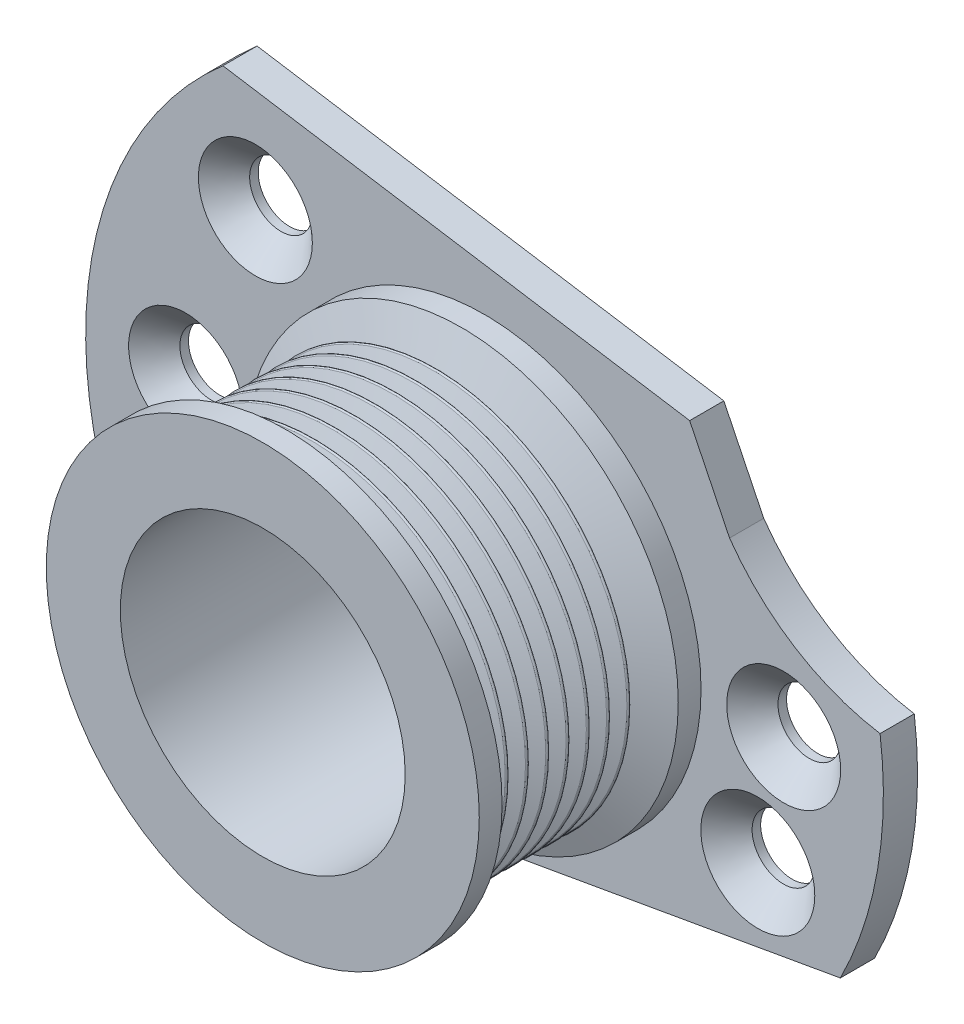
SolidWorks part; units mm, degrees
material "6061-T6 (SS)"
ref_plane "Plano frontal" through (0, 0, 0) normal (0, 0, 1) x (1, 0, 0)
ref_plane "Plano superior" through (0, 0, 0) normal (0, 1, 0) x (1, 0, 0)
ref_plane "Plano direito" through (0, 0, 0) normal (1, 0, 0) x (0, 0, -1)
sketch "Esboço1" plane through (0, 0, 0) normal (0, 0, 1) x (1, 0, 0)
  line L11 (43.3076, 46.4505) -> (-51.3624, 61.4448) construction
  line L12 (-51.3624, 61.4448) -> (-78.1924, 55.7367) construction
  line L13 (-78.1924, 55.7367) -> (-90.1924, 31.0704) construction
  line L14 (-90.1924, 31.0704) -> (-90.1924, -31.3604) construction
  line L15 (-90.1924, -31.3604) -> (-74.4201, -50.1572) construction
  line L16 (-74.4201, -50.1572) -> (-51.3624, -58.5495) construction
  line L17 (-51.3624, -58.5495) -> (88.1376, -33.9518) construction
  line L18 (88.1376, -33.9518) -> (98.8391, -4.5495) construction
  line L19 (98.8391, -4.5495) -> (100.3076, 16.4505) construction
  line L20 (100.3076, 16.4505) -> (80.9144, 14.4122) construction
  line L21 (50.8276, 31.0704) -> (43.3076, 46.4505) construction
  line L22 (-45.9193, 52.8338) -> (36, 39.8591)
  line L23 (-47.856, -51.0862) -> (62.4425, -31.6376)
  line L25 (0, 0) -> (21.8104, 0) construction
  line L26 (0, 0) -> (0, 85.1678) construction
  line L29 (36, 39.8591) -> (43, 25.507)
  line L30 (-23.7282, -46.8318) -> (0, 0) construction
  line L31 (0, 0) -> (-19.6692, 48.6762) construction
  line L32 (0, 0) -> (-40.2173, 33.7463) construction
  line L33 (0, 0) -> (-43.0055, -30.1128) construction
  line L34 (0, 0) -> (7.4749, 0) construction
  line L37 (0, 0) -> (52.5, 0) construction
  line L38 (0, 0) -> (47.9611, -21.3537) construction
  arc A2 (50.8276, 31.0704) -> (80.9144, 14.4122) centre (77.7786, 44.2479) ccw construction
  circle A3 centre (0, 0) radius 36 construction
  arc A5 (-45.9193, 52.8338) -> (-47.856, -51.0862) centre (0, 0) ccw
  arc A7 (43, 25.507) -> (69.419, 9) centre (75.7319, 48.4987) ccw
  arc A8 (69.419, 9) -> (62.4425, -31.6376) centre (0, 0) cw
  circle A9 centre (0, 0) radius 37.5 construction
  circle A11 centre (0, 0) radius 25
  circle A12 centre (0, 0) radius 37.5 construction
  circle A13 centre (0, 0) radius 52.5 construction
  point P14 (-40.2173, 33.7463)
  point P15 (-52.4619, 2)
  point P17 (-43.0055, -30.1128)
  point P18 (-19.6692, 48.6762)
  point P36 (-23.7282, -46.8318)
  point P40 (52.5, 0)
  point P41 (47.9611, -21.3537)
  dimension "D3" = 70
  dimension "D4" = 45
  dimension "D10" = 40
  dimension "D11" = 72
  dimension "D12" = 75
  dimension "D13" = 50
  dimension "D14" = 15
  dimension "D1" = 10
  dimension "D2" = 9
  dimension "D5" = 42
  dimension "D6" = 26
  dimension "D7" = 36
  dimension "D8" = 9
  dimension "D9" = 43
  dimension "D15" = 35
  dimension "D16" = 40
  dimension "D18" = 24
  dimension "D19" = 2
extrude "Ressalto-extrusão1" add sketch "Esboço1" along normal blind 6 contours A8 A7 L29 L22 A5 L23 A11
hole_wizard "Escareado para parafuso com cabeça escareada chata de M101" positions "Esboço3" profile "Esboço4" countersink size "M10" standard "ISO" end condition through all
sketch "Esboço3" plane through (0, 0, 6) normal (0, 0, 1) x (1, 0, 0)
  point P0 (52.5, 0)
  point P3 (47.9611, -21.3537)
  point P6 (-43.0055, -30.1128)
  point P9 (-40.2173, 33.7463)
  point P12 (-52.4619, 2)
sketch "Esboço4" plane through (52.5, 0, 6) normal (1, 0, 0) x (0, -1, 0)
  line L0 (0, 0) -> (0, 6)
  line L1 (0, 6) -> (5.5, 6)
  line L2 (5.5, 6) -> (5.5, 4.5)
  line L3 (5.5, 4.5) -> (10, 0)
  line L5 (10, 0) -> (0, 0)
  line L6 (-5.5, 4.5) -> (-10, 0) construction
  line L11 (0, -6.35) -> (0, 107.95) construction
  dimension "Thru Hole Dia." = 11
  dimension "Thru Hole Depth" = 6
  dimension "Near C'Sink Dia." = 20
  dimension "Near C'Sink Angle" = 90
sketch "Esboço5" plane through (0, 0, 0) normal (1, 0, 0) x (0, 0, -1)
  line L0 (-6, 25) -> (-44.92, 25)
  line L1 (-44.92, 25) -> (-44.92, 38)
  line L2 (-44.92, 38) -> (-40.92, 38)
  line L3 (-40.92, 38) -> (-38.3898, 31.0485)
  line L5 (-37.4502, 31.0485) -> (-36.3749, 34.0026)
  line L6 (-35.9051, 34.0026) -> (-34.8298, 31.0485)
  line L7 (-33.8902, 31.0485) -> (-32.8149, 34.0026)
  line L8 (-32.3451, 34.0026) -> (-31.2698, 31.0485)
  line L9 (-30.3302, 31.0485) -> (-29.2549, 34.0026)
  line L10 (-28.7851, 34.0026) -> (-27.7098, 31.0485)
  line L11 (-26.7702, 31.0485) -> (-25.6949, 34.0026)
  line L12 (-25.2251, 34.0026) -> (-24.1498, 31.0485)
  line L13 (-23.2102, 31.0485) -> (-22.1349, 34.0026)
  line L14 (-21.6651, 34.0026) -> (-20.5898, 31.0485)
  line L15 (-19.6502, 31.0485) -> (-18.5749, 34.0026)
  line L16 (-18.1051, 34.0026) -> (-17.0298, 31.0485)
  line L17 (-16.0902, 31.0485) -> (-15.0149, 34.0026)
  line L18 (-14.5451, 34.0026) -> (-13.4698, 31.0485)
  line L19 (-12.5302, 31.0485) -> (-10, 38)
  line L20 (-10, 38) -> (-6, 38)
  line L21 (-6, 52.8338) -> (-6, 39.8591) construction
  line L22 (-6, 38) -> (-6, 25)
  arc A0 (-15.0149, 34.0026) -> (-14.5451, 34.0026) centre (-14.78, 33.9171) cw
  arc A1 (-18.1051, 34.0026) -> (-18.5749, 34.0026) centre (-18.34, 33.9171) ccw
  arc A2 (-21.6651, 34.0026) -> (-22.1349, 34.0026) centre (-21.9, 33.9171) ccw
  arc A3 (-25.2251, 34.0026) -> (-25.6949, 34.0026) centre (-25.46, 33.9171) ccw
  arc A4 (-28.7851, 34.0026) -> (-29.2549, 34.0026) centre (-29.02, 33.9171) ccw
  arc A5 (-32.3451, 34.0026) -> (-32.8149, 34.0026) centre (-32.58, 33.9171) ccw
  arc A6 (-35.9051, 34.0026) -> (-36.3749, 34.0026) centre (-36.14, 33.9171) ccw
  arc A7 (-13.4698, 31.0485) -> (-12.5302, 31.0485) centre (-13, 31.2195) ccw
  arc A8 (-17.0298, 31.0485) -> (-16.0902, 31.0485) centre (-16.56, 31.2195) ccw
  arc A9 (-20.5898, 31.0485) -> (-19.6502, 31.0485) centre (-20.12, 31.2195) ccw
  arc A10 (-24.1498, 31.0485) -> (-23.2102, 31.0485) centre (-23.68, 31.2195) ccw
  arc A11 (-27.7098, 31.0485) -> (-26.7702, 31.0485) centre (-27.24, 31.2195) ccw
  arc A12 (-31.2698, 31.0485) -> (-30.3302, 31.0485) centre (-30.8, 31.2195) ccw
  arc A13 (-34.8298, 31.0485) -> (-33.8902, 31.0485) centre (-34.36, 31.2195) ccw
  arc A14 (-38.3898, 31.0485) -> (-37.4502, 31.0485) centre (-37.92, 31.2195) ccw
  point P8 (-36.14, 34.6481)
  point P9 (-32.58, 34.6481)
  point P11 (-29.02, 34.6481)
  point P13 (-25.46, 34.6481)
  point P15 (-21.9, 34.6481)
  point P17 (-18.34, 34.6481)
  point P19 (-14.78, 34.6481)
  point P56 (-13, 29.7576)
  point P59 (-16.56, 29.7576)
  point P62 (-20.12, 29.7576)
  point P65 (-23.68, 29.7576)
  point P68 (-27.24, 29.7576)
  point P71 (-30.8, 29.7576)
  point P74 (-34.36, 29.7576)
  point P77 (-37.92, 29.7576)
  dimension "D8" = 0.25
  dimension "D9" = 0.5
  dimension "D1" = 13
  dimension "D2" = 40
  dimension "D3" = 20
  dimension "D4" = 3.56
  dimension "D5" = 4
  dimension "D6" = 4
  dimension "D7" = 3
revolve "Revolução1" add sketch "Esboço5" angle 360 about axis through (0, 0, 6) along (0, 0, -1)
mirror "Espelhar1" [suppressed]
delete or keep bodies "Corpo-Excluir/Manter 1" [suppressed] type delete bodies bodies 103
